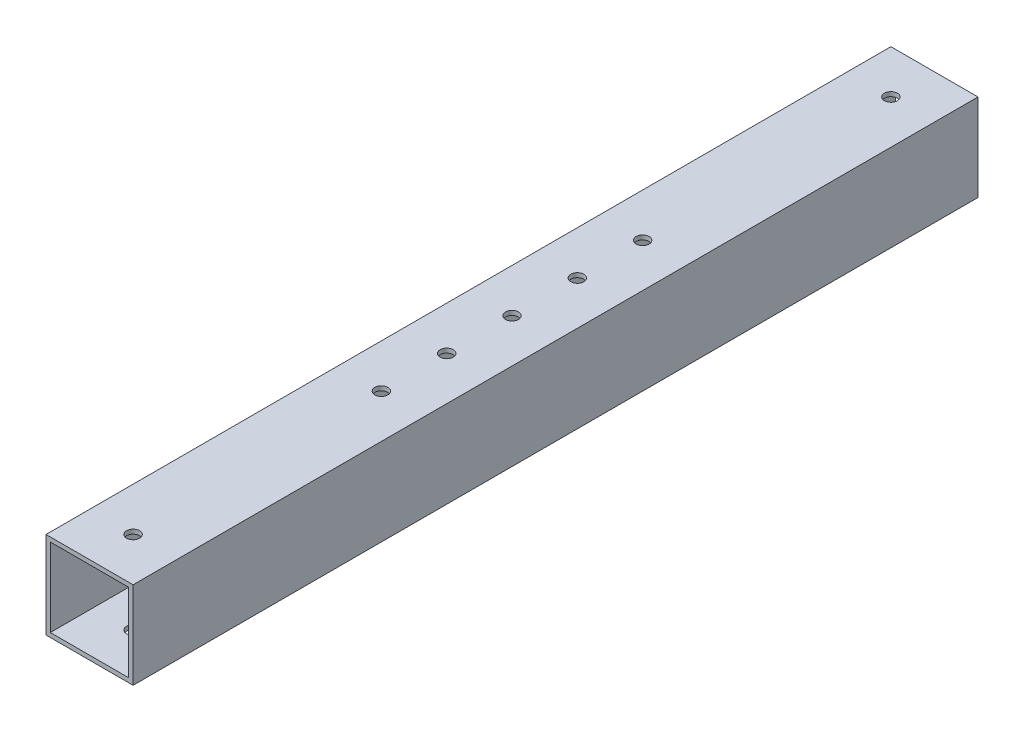
SolidWorks part; units mm, degrees
ref_plane "前视基准面" through (0, 0, 0) normal (0, 0, 1) x (1, 0, 0)
ref_plane "上视基准面" through (0, 0, 0) normal (0, 1, 0) x (1, 0, 0)
ref_plane "右视基准面" through (0, 0, 0) normal (1, 0, 0) x (0, 0, -1)
sketch "草图1" plane through (0, 0, 0) normal (0, 0, 1) x (1, 0, 0)
  line L1 (-9, 9) -> (9, 9)
  line L2 (-9, 9) -> (-9, -9)
  line L3 (-9, -9) -> (9, -9)
  line L4 (9, 9) -> (9, -9)
  line L5 (0, -9) -> (0, 9) construction
  line L6 (-9, 0) -> (9, 0) construction
  line L7 (-10, 10) -> (10, 10)
  line L8 (-10, 10) -> (-10, -10)
  line L9 (-10, -10) -> (10, -10)
  line L10 (10, 10) -> (10, -10)
  line L11 (0, -10) -> (0, 10) construction
  line L12 (-10, 0) -> (10, 0) construction
  point P0 (0, 0)
  point P4 (0, 0)
  dimension "D1" = 20
  dimension "D2" = 18
  dimension "D3" = 20
  dimension "D4" = 18
extrude "凸台-拉伸1" add sketch "草图1" along normal mid plane 194
sketch "草图2" plane through (0, 10, 0) normal (0, 1, 0) x (1, 0, 0)
  line L0 (0, 0) -> (31.4945, 0) construction
  line L1 (0, 0) -> (0, 88.3718) construction
  line L2 (10, 97) -> (-10, 97) construction
  circle A0 centre (0, 87) radius 1.5
  circle A1 centre (0, -87) radius 1.5
  circle A2 centre (0, 0) radius 1.5
  circle A3 centre (0, 15) radius 1.5
  circle A4 centre (0, 30) radius 1.5
  circle A5 centre (0, -30) radius 1.5
  circle A6 centre (0, -15) radius 1.5
  dimension "D1" = 3
  dimension "D3" = 3
  dimension "D4" = 3
  dimension "D7" = 3
  dimension "D2" = 10
  dimension "D5" = 15
  dimension "D6" = 15
extrude "切除-拉伸1" cut sketch "草图2" against normal blind 166
